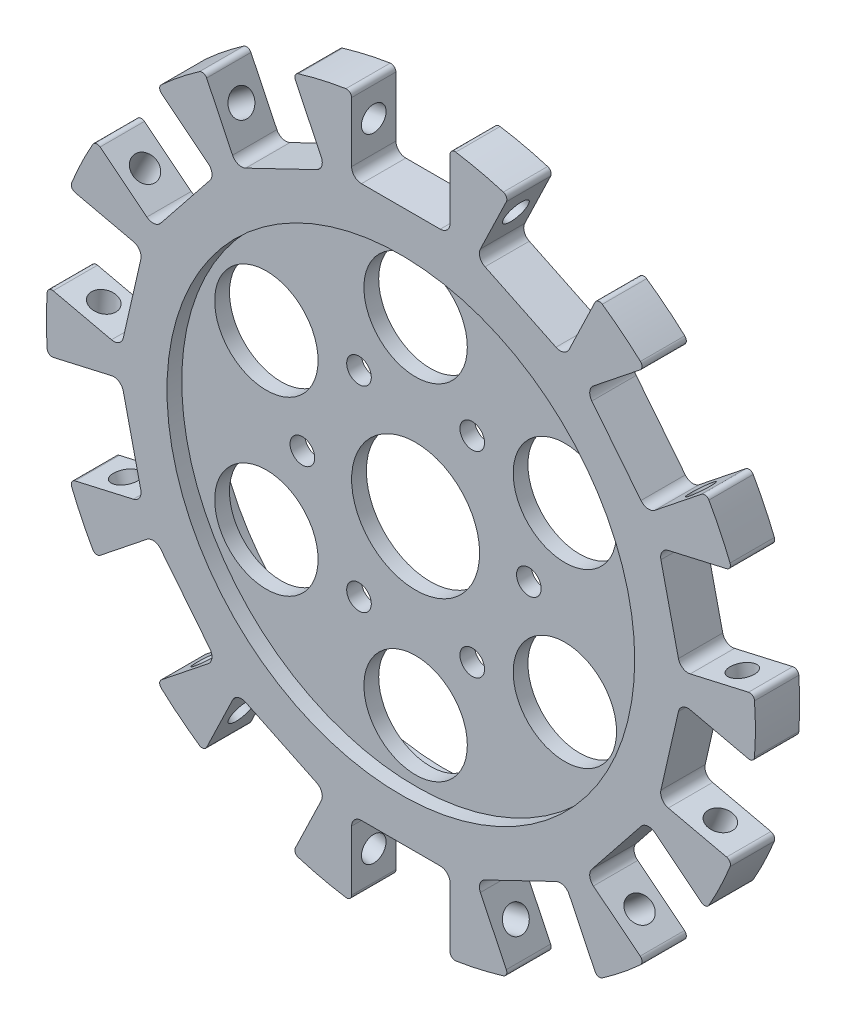
SolidWorks part; units mm, degrees
material "AISI 304"
ref_plane "前视基准面" through (0, 0, 0) normal (0, 0, 1) x (1, 0, 0)
ref_plane "上视基准面" through (0, 0, 0) normal (0, 1, 0) x (1, 0, 0)
ref_plane "右视基准面" through (0, 0, 0) normal (1, 0, 0) x (0, 0, -1)
sketch "草图1" plane through (0, 0, 0) normal (0, 0, 1) x (1, 0, 0)
  line L0 (0, -1000) -> (0, 49000) construction
  line L1 (-10, 58) -> (-10, 71.3022)
  line L2 (10, 58) -> (10, 71.3022)
  line L3 (0, 56) -> (8, 56)
  line L4 (0, 56) -> (-8, 56)
  line L5 (34.1749, 47.9174) -> (39.9465, 59.9022)
  line L6 (16.1556, 56.595) -> (21.9272, 68.5799)
  line L7 (24.2975, 50.4543) -> (31.5052, 46.9832)
  line L8 (24.2975, 50.4543) -> (17.0897, 53.9253)
  line L9 (51.5811, 28.3441) -> (61.9812, 36.6379)
  line L10 (39.1113, 43.9807) -> (49.5114, 52.2745)
  line L11 (43.7826, 34.9154) -> (48.7705, 28.6608)
  line L12 (43.7826, 34.9154) -> (38.7946, 41.1701)
  line L13 (58.771, 3.1569) -> (71.7397, 6.1169)
  line L14 (54.3206, 22.6555) -> (67.2893, 25.6155)
  line L15 (54.596, 12.4612) -> (56.3761, 4.6617)
  line L16 (54.596, 12.4612) -> (52.8158, 20.2606)
  line L17 (54.3206, -22.6555) -> (67.2893, -25.6155)
  line L18 (58.771, -3.1569) -> (71.7397, -6.1169)
  line L19 (54.596, -12.4612) -> (52.8158, -20.2606)
  line L20 (54.596, -12.4612) -> (56.3761, -4.6617)
  line L21 (39.1113, -43.9807) -> (49.5114, -52.2745)
  line L22 (51.5811, -28.3441) -> (61.9812, -36.6379)
  line L23 (43.7826, -34.9154) -> (38.7946, -41.1701)
  line L24 (43.7826, -34.9154) -> (48.7705, -28.6608)
  line L25 (16.1556, -56.595) -> (21.9272, -68.5799)
  line L26 (34.1749, -47.9174) -> (39.9465, -59.9022)
  line L27 (24.2975, -50.4543) -> (17.0897, -53.9253)
  line L28 (24.2975, -50.4543) -> (31.5052, -46.9832)
  line L29 (-10, -58) -> (-10, -71.3022)
  line L30 (10, -58) -> (10, -71.3022)
  line L31 (0, -56) -> (-8, -56)
  line L32 (0, -56) -> (8, -56)
  line L33 (-34.1749, -47.9174) -> (-39.9465, -59.9022)
  line L34 (-16.1556, -56.595) -> (-21.9272, -68.5799)
  line L35 (-24.2975, -50.4543) -> (-31.5052, -46.9832)
  line L36 (-24.2975, -50.4543) -> (-17.0897, -53.9253)
  line L37 (-51.5811, -28.3441) -> (-61.9812, -36.6379)
  line L38 (-39.1113, -43.9807) -> (-49.5114, -52.2745)
  line L39 (-43.7826, -34.9154) -> (-48.7705, -28.6608)
  line L40 (-43.7826, -34.9154) -> (-38.7946, -41.1701)
  line L41 (-58.771, -3.1569) -> (-71.7397, -6.1169)
  line L42 (-54.3206, -22.6555) -> (-67.2893, -25.6155)
  line L43 (-54.596, -12.4612) -> (-56.3761, -4.6617)
  line L44 (-54.596, -12.4612) -> (-52.8158, -20.2606)
  line L45 (-54.3206, 22.6555) -> (-67.2893, 25.6155)
  line L46 (-58.771, 3.1569) -> (-71.7397, 6.1169)
  line L47 (-54.596, 12.4612) -> (-52.8158, 20.2606)
  line L48 (-54.596, 12.4612) -> (-56.3761, 4.6617)
  line L49 (-39.1113, 43.9807) -> (-49.5114, 52.2745)
  line L50 (-51.5811, 28.3441) -> (-61.9812, 36.6379)
  line L51 (-43.7826, 34.9154) -> (-38.7946, 41.1701)
  line L52 (-43.7826, 34.9154) -> (-48.7705, 28.6608)
  line L53 (-16.1556, 56.595) -> (-21.9272, 68.5799)
  line L54 (-34.1749, 47.9174) -> (-39.9465, 59.9022)
  line L55 (-24.2975, 50.4543) -> (-17.0897, 53.9253)
  line L56 (-24.2975, 50.4543) -> (-31.5052, 46.9832)
  line L57 (0, 0) -> (0, 56) construction
  line L58 (0, 0) -> (24.2975, 50.4543) construction
  arc A0 (-10, 71.3022) -> (-21.9272, 68.5799) centre (0, 0) ccw
  arc A1 (31.5052, 46.9832) -> (34.1749, 47.9174) centre (32.373, 48.7851) ccw
  arc A2 (8, 56) -> (10, 58) centre (8, 58) ccw
  arc A3 (-8, 56) -> (-10, 58) centre (-8, 58) cw
  arc A4 (17.0897, 53.9253) -> (16.1556, 56.595) centre (17.9575, 55.7273) cw
  arc A5 (48.7705, 28.6608) -> (51.5811, 28.3441) centre (50.3341, 29.9078) ccw
  arc A6 (38.7946, 41.1701) -> (39.1113, 43.9807) centre (40.3583, 42.4171) cw
  arc A7 (56.3761, 4.6617) -> (58.771, 3.1569) centre (58.326, 5.1068) ccw
  arc A8 (52.8158, 20.2606) -> (54.3206, 22.6555) centre (54.7657, 20.7056) cw
  arc A9 (52.8158, -20.2606) -> (54.3206, -22.6555) centre (54.7657, -20.7056) ccw
  arc A10 (56.3761, -4.6617) -> (58.771, -3.1569) centre (58.326, -5.1068) cw
  arc A11 (38.7946, -41.1701) -> (39.1113, -43.9807) centre (40.3583, -42.4171) ccw
  arc A12 (48.7705, -28.6608) -> (51.5811, -28.3441) centre (50.3341, -29.9078) cw
  arc A13 (17.0897, -53.9253) -> (16.1556, -56.595) centre (17.9575, -55.7273) ccw
  arc A14 (31.5052, -46.9832) -> (34.1749, -47.9174) centre (32.373, -48.7851) cw
  arc A15 (-8, -56) -> (-10, -58) centre (-8, -58) ccw
  arc A16 (8, -56) -> (10, -58) centre (8, -58) cw
  arc A17 (-31.5052, -46.9832) -> (-34.1749, -47.9174) centre (-32.373, -48.7851) ccw
  arc A18 (-17.0897, -53.9253) -> (-16.1556, -56.595) centre (-17.9575, -55.7273) cw
  arc A19 (-48.7705, -28.6608) -> (-51.5811, -28.3441) centre (-50.3341, -29.9078) ccw
  arc A20 (-38.7946, -41.1701) -> (-39.1113, -43.9807) centre (-40.3583, -42.4171) cw
  arc A21 (-56.3761, -4.6617) -> (-58.771, -3.1569) centre (-58.326, -5.1068) ccw
  arc A22 (-52.8158, -20.2606) -> (-54.3206, -22.6555) centre (-54.7657, -20.7056) cw
  arc A23 (-52.8158, 20.2606) -> (-54.3206, 22.6555) centre (-54.7657, 20.7056) ccw
  arc A24 (-56.3761, 4.6617) -> (-58.771, 3.1569) centre (-58.326, 5.1068) cw
  arc A25 (-38.7946, 41.1701) -> (-39.1113, 43.9807) centre (-40.3583, 42.4171) ccw
  arc A26 (-48.7705, 28.6608) -> (-51.5811, 28.3441) centre (-50.3341, 29.9078) cw
  arc A27 (-17.0897, 53.9253) -> (-16.1556, 56.595) centre (-17.9575, 55.7273) ccw
  arc A28 (-31.5052, 46.9832) -> (-34.1749, 47.9174) centre (-32.373, 48.7851) cw
  arc A29 (-39.9465, 59.9022) -> (-49.5114, 52.2745) centre (0, 0) ccw
  arc A30 (-61.9812, 36.6379) -> (-67.2893, 25.6155) centre (0, 0) ccw
  arc A31 (-71.7397, 6.1169) -> (-71.7397, -6.1169) centre (0, 0) ccw
  arc A32 (-67.2893, -25.6155) -> (-61.9812, -36.6379) centre (0, 0) ccw
  arc A33 (-49.5114, -52.2745) -> (-39.9465, -59.9022) centre (0, 0) ccw
  arc A34 (-21.9272, -68.5799) -> (-10, -71.3022) centre (0, 0) ccw
  arc A35 (10, -71.3022) -> (21.9272, -68.5799) centre (0, 0) ccw
  arc A36 (39.9465, -59.9022) -> (49.5114, -52.2745) centre (0, 0) ccw
  arc A37 (61.9812, -36.6379) -> (67.2893, -25.6155) centre (0, 0) ccw
  arc A38 (71.7397, -6.1169) -> (71.7397, 6.1169) centre (0, 0) ccw
  arc A39 (67.2893, 25.6155) -> (61.9812, 36.6379) centre (0, 0) ccw
  arc A40 (49.5114, 52.2745) -> (39.9465, 59.9022) centre (0, 0) ccw
  arc A41 (21.9272, 68.5799) -> (10, 71.3022) centre (0, 0) ccw
  dimension "D1" = 144
  dimension "D2" = 25.714
  dimension "D5" = 2
  dimension "D6" = 2
  dimension "D3" = 10
  dimension "D4" = 10
  dimension "D7" = 56
extrude "拉伸1" add sketch "草图1" along normal mid plane 9
fillet "圆角1" radius 1 28 edges at (10, 71.3022, 0) (21.9272, 68.5799, 0) (39.9465, 59.9022, 0) (49.5114, 52.2745, 0) (61.9812, 36.6379, 0) (67.2893, 25.6155, 0) (71.7397, 6.1169, 0) (71.7397, -6.1169, 0) (67.2893, -25.6155, 0) (61.9812, -36.6379, 0) (49.5114, -52.2745, 0) (39.9465, -59.9022, 0) (21.9272, -68.5799, 0) (10, -71.3022, 0) (-10, -71.3022, 0) (-21.9272, -68.5799, 0) (-39.9465, -59.9022, 0) (-49.5114, -52.2745, 0) (-61.9812, -36.6379, 0) (-67.2893, -25.6155, 0) (-71.7397, -6.1169, 0) (-71.7397, 6.1169, 0) (-67.2893, 25.6155, 0) (-61.9812, 36.6379, 0) (-49.5114, 52.2745, 0) (-39.9465, 59.9022, 0) (-21.9272, 68.5799, 0) (-10, 71.3022, 0)
sketch "草图2" plane through (0, 0, 4.5) normal (0, 0, 1) x (1, 0, 0)
  circle A0 centre (0, 0) radius 47.5
  dimension "D1" = 95
extrude "拉伸2" cut sketch "草图2" against normal blind 3
sketch "草图3" plane through (0, 0, -4.5) normal (0, 0, -1) x (-1, 0, 0)
  circle A0 centre (0, 0) radius 47.5
  dimension "D1" = 95
extrude "拉伸3" cut sketch "草图3" against normal blind 3
sketch "草图4" plane through (0, 0, 1.5) normal (0, 0, 1) x (1, 0, 0)
  line L0 (0.001, 0) -> (0, 35) construction
  circle A0 centre (0, 0) radius 13
  circle A1 centre (0, 35) radius 10.5
  circle A2 centre (0, 0) radius 35 construction
  circle A3 centre (30.3114, 17.5009) radius 10.5
  circle A4 centre (30.3124, -17.4991) radius 10.5
  circle A5 centre (0.002, -35) radius 10.5
  circle A6 centre (-30.3094, -17.5009) radius 10.5
  circle A7 centre (-30.3104, 17.4991) radius 10.5
  dimension "D1" = 26
  dimension "D2" = 70
  dimension "D3" = 21
  dimension "D4" = 35
extrude "拉伸4" cut sketch "草图4" against normal through all
sketch "草图5" plane through (0, 0, 1.5) normal (0, 0, 1) x (1, 0, 0)
  line L1 (-11.5, -19.9186) -> (11.5, -19.9186) construction
  line L2 (11.5, -19.9186) -> (23, 0) construction
  line L3 (23, 0) -> (11.5, 19.9186) construction
  line L4 (11.5, 19.9186) -> (-11.5, 19.9186) construction
  line L5 (-11.5, 19.9186) -> (-23, 0) construction
  line L6 (-23, 0) -> (-11.5, -19.9186) construction
  circle A0 centre (0, 0) radius 23 construction
  circle A1 centre (0, 0) radius 19.9186 construction
  circle A2 centre (-11.5, 19.9186) radius 2.5
  circle A3 centre (11.5, 19.9186) radius 2.5
  circle A4 centre (23, 0) radius 2.5
  circle A5 centre (11.5, -19.9186) radius 2.5
  circle A6 centre (-11.5, -19.9186) radius 2.5
  circle A7 centre (-23, 0) radius 2.5
extrude "拉伸5" cut sketch "草图5" against normal through all
sketch "草图6" plane through (0, 0, 0) normal (0, 0, 1) x (1, 0, 0)
  circle A0 centre (0, 0) radius 65
  dimension "D1" = 130
sketch "草图7" plane through (0, 0, 0) normal (0, 1, 0) x (1, 0, 0)
  line L0 (-65, 0) -> (65, 0) construction
  circle A0 centre (-65, 0) radius 2.5
  dimension "D1" = 5
sweep "切除-扫描1" cut profiles "草图7" path "草图6"
sketch "草图8" plane through (0, 0, 0) normal (0, 0, 1) x (1, 0, 0)
  circle A0 centre (0, 0) radius 65
  dimension "D1" = 130
